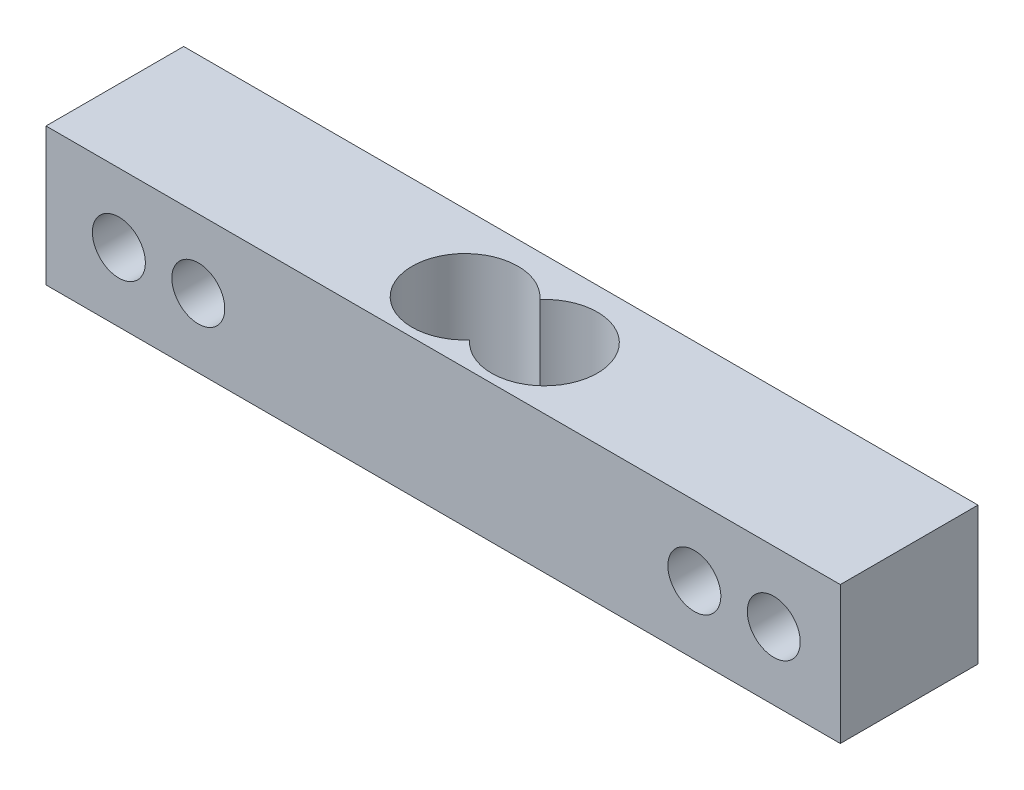
SolidWorks part; units mm, degrees
ref_plane "Front Plane" through (0, 0, 0) normal (0, 0, 1) x (1, 0, 0)
ref_plane "Top Plane" through (0, 0, 0) normal (0, 1, 0) x (1, 0, 0)
ref_plane "Right Plane" through (0, 0, 0) normal (1, 0, 0) x (0, 0, -1)
sketch "Sketch1" plane through (0, 0, 0) normal (0, 0, 1) x (1, 0, 0)
  line L1 (37.5, 6.5) -> (-37.5, 6.5)
  line L2 (37.5, 6.5) -> (37.5, -6.5)
  line L3 (37.5, -6.5) -> (-37.5, -6.5)
  line L4 (-37.5, 6.5) -> (-37.5, -6.5)
  line L5 (37.5, 6.5) -> (-37.5, -6.5) construction
  line L6 (37.5, -6.5) -> (-37.5, 6.5) construction
  point P0 (0, 0)
  dimension "D1" = 13
  dimension "D2" = 75
extrude "Boss-Extrude1" add sketch "Sketch1" along normal blind 13
ref_plane "Plane1" through (-37.5, -6.5, 0) normal (1, 0, 0) x (0, 0, -1)
sketch "Sketch3" plane through (0, 0, 0) normal (0, 0, 1) x (1, 0, 0)
  line L0 (-30.6191, 0.0007) -> (-23.1191, 0.0007) construction
  line L1 (-23.1191, 0.0007) -> (-30.6191, 0.0007) construction
  line L2 (23.7163, -0.0967) -> (31.2163, -0.0967) construction
  line L3 (31.2163, -0.0967) -> (23.7163, -0.0967) construction
  circle A0 centre (31.2163, -0.0967) radius 2.5
  circle A1 centre (23.7163, -0.0967) radius 2.5
  circle A2 centre (-23.1191, 0.0007) radius 2.5
  circle A3 centre (-30.6191, 0.0007) radius 2.5
  dimension "D1" = 5
  dimension "D2" = 5
  dimension "D3" = 5
  dimension "D4" = 5
  dimension "D5" = 7.5
  dimension "D6" = 7.5
extrude "Cut-Extrude4" cut sketch "Sketch3" along normal up to surface (13 mm away) up to face at (0, 0, 13)
sketch "Sketch4" plane through (0, 6.5, 0) normal (0, 1, 0) x (1, 0, 0)
  line L0 (0, -0.66) -> (0, -3.8772)
  line L1 (0, -13.7088) -> (0, -10.4916)
  line L2 (-1.25, -7.1844) -> (-1.2777, -7.1844)
  line L3 (0, -10.4916) -> (0, -13.7088)
  line L4 (-1.25, -7.1844) -> (-1.2777, -7.1844)
  line L5 (0, -3.8772) -> (0, 6.64)
  arc A0 (0, -3.8772) -> (0, -10.4916) centre (-3.75, -7.1844) ccw
  arc A1 (0, -10.4916) -> (0, -3.8772) centre (3.75, -7.1844) ccw
  point P3 (1187.6918, 1027.3891)
  dimension "D1" = 10
  dimension "D2" = 10
  dimension "D3" = 7.5
extrude "Cut-Extrude5" cut sketch "Sketch4" against normal blind 13
